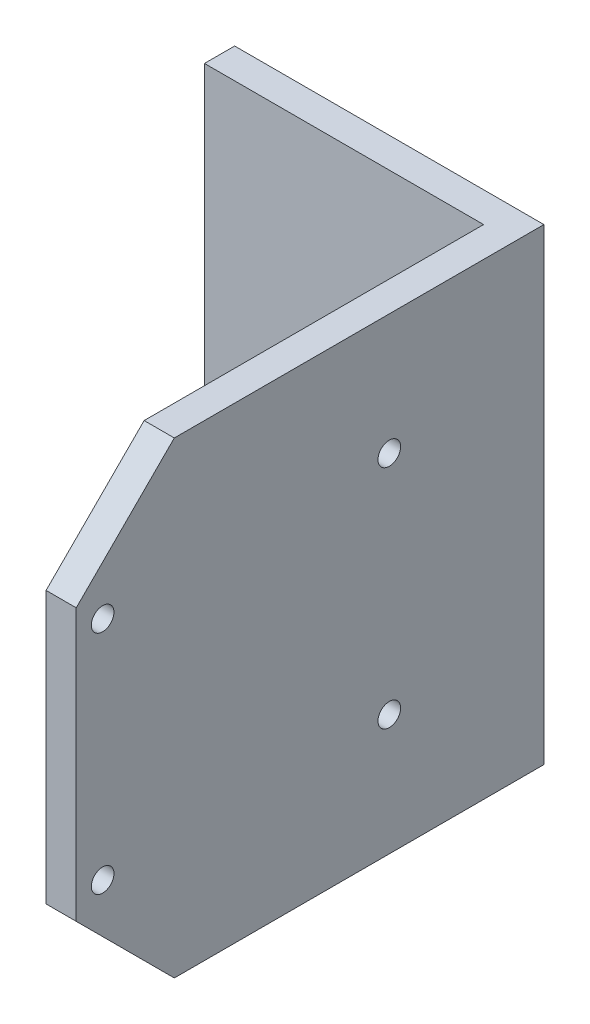
SolidWorks part; units mm, degrees
ref_plane "前视基准面" through (0, 0, 0) normal (0, 0, 1) x (1, 0, 0)
ref_plane "上视基准面" through (0, 0, 0) normal (0, 1, 0) x (1, 0, 0)
ref_plane "右视基准面" through (0, 0, 0) normal (1, 0, 0) x (0, 0, -1)
other "Configuration Table"
sketch "草图1" plane through (0, 0, 0) normal (0, 1, 0) x (1, 0, 0)
  line L0 (-30.126, 43.1575) -> (10.874, 43.1575)
  line L1 (10.874, 43.1575) -> (10.874, -18.8425)
  line L2 (10.874, -18.8425) -> (6.874, -18.8425)
  line L3 (6.874, -18.8425) -> (6.874, 39.1575)
  line L4 (6.874, 39.1575) -> (-30.126, 39.1575)
  line L5 (-30.126, 39.1575) -> (-30.126, 43.1575)
  dimension "D1" = 41
  dimension "D2" = 62
  dimension "D3" = 4
  dimension "D4" = 4
extrude "凸台-拉伸1" add sketch "草图1" along normal mid plane 62
ref_plane "基准面1" through (10.874, 0, 0) normal (1, 0, 0) x (0, 0, -1)
sketch "草图2" plane through (10.874, 0, 0) normal (1, 0, 0) x (0, 0, -1)
  line L0 (-18.8425, 31) -> (-18.8425, -31) construction
  line L1 (-18.8425, -31) -> (43.1575, -31) construction
  line L2 (43.1575, 31) -> (43.1575, -31) construction
  line L3 (-18.8425, 31) -> (43.1575, 31) construction
  line L4 (-18.8425, 31) -> (-18.8425, -31)
  line L5 (-18.8425, -31) -> (43.1575, -31)
  line L6 (43.1575, 31) -> (43.1575, -31)
  line L7 (-18.8425, 31) -> (43.1575, 31)
  line L8 (43.1575, 0) -> (-18.8425, 0)
  line L9 (22.6575, 0) -> (22.6575, -15)
  line L12 (-18.8425, -18) -> (-5.8425, -31)
  line L13 (-18.8425, 18) -> (-5.8425, 31)
  circle A0 centre (22.6575, -15) radius 1.5
  circle A1 centre (22.6575, 15) radius 1.5
  circle A2 centre (-15.3425, 15) radius 1.5
  circle A3 centre (-15.3425, -15) radius 1.5
  dimension "D2" = 18
  dimension "D1" = 41.5
  dimension "D3" = 30
extrude "切除-拉伸2" cut sketch "草图2" against normal blind 10
ref_plane "基准面2" through (0, 0, -43.1575) normal (0, 0, -1) x (-1, 0, 0)
